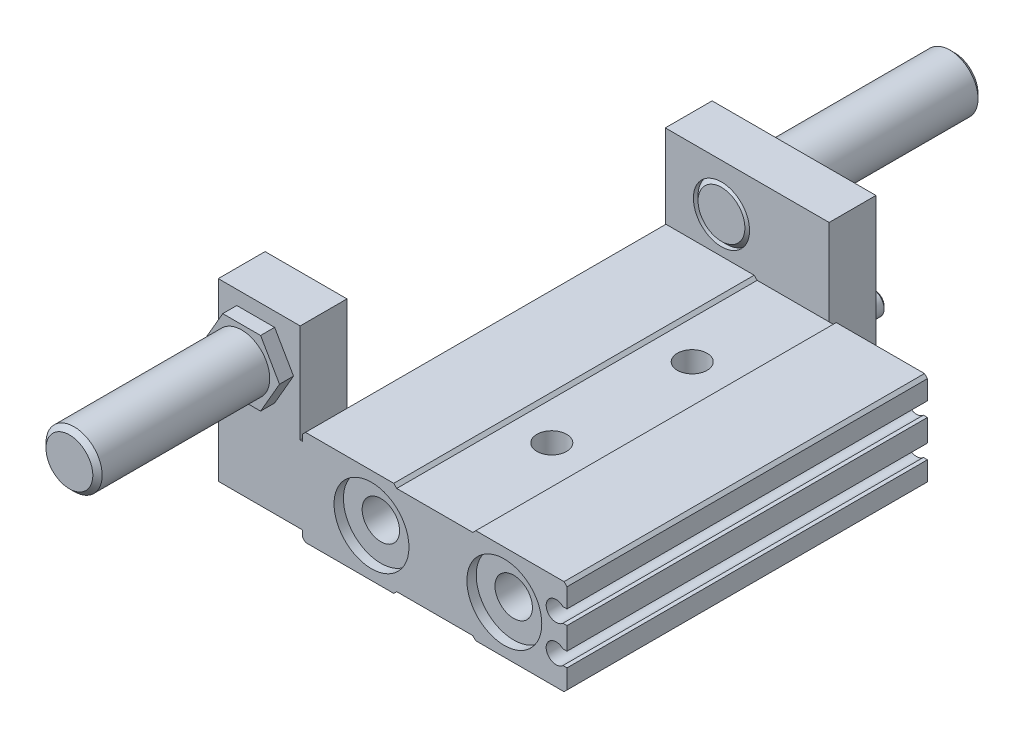
SolidWorks part; units mm, degrees
ref_plane "Front" through (0, 0, 0) normal (0, 0, 1) x (1, 0, 0)
ref_plane "Top" through (0, 0, 0) normal (0, 1, 0) x (1, 0, 0)
ref_plane "Right" through (0, 0, 0) normal (1, 0, 0) x (0, 0, -1)
ref_plane "Plane4" through (0, 0, 0) normal (0, 0, 1) x (-1, 0, 0)
sketch "Sketch1" plane through (0, 0, 51.15) normal (0, 0, 1) x (-1, 0, 0)
  line L0 (27.615, 10.1854) -> (28.25, 9.5504)
  line L1 (-8.128, 9.5504) -> (8.128, 9.5504)
  line L2 (27.615, 10.1854) -> (8.763, 10.1854)
  line L3 (-8.763, 10.1854) -> (-27.615, 10.1854)
  line L4 (8.128, 9.5504) -> (8.763, 10.1854)
  line L5 (-8.128, 9.5504) -> (-8.763, 10.1854)
  line L6 (-28.25, 9.5504) -> (-28.25, 5.4483)
  line L7 (-28.25, -9.5504) -> (-27.615, -10.1854)
  line L8 (-8.128, -9.5504) -> (-8.763, -10.1854)
  line L9 (-28.25, 2.3749) -> (-28.25, -2.3749)
  line L10 (-28.25, -5.4483) -> (-28.25, -9.5504)
  line L11 (-28.25, 9.5504) -> (-27.615, 10.1854)
  line L12 (28.25, 9.5504) -> (28.25, -9.5504)
  line L14 (-50, 0) -> (50, 0) construction
  line L15 (-8.763, -10.1854) -> (-27.615, -10.1854)
  line L16 (-27.3844, -5.4483) -> (-28.25, -5.4483)
  line L18 (-8.128, -9.5504) -> (8.128, -9.5504)
  line L19 (8.128, -9.5504) -> (8.763, -10.1854)
  line L20 (28.25, -9.5504) -> (27.615, -10.1854)
  line L22 (-28.25, 0) -> (28.25, 0) construction
  line L23 (0, 0) -> (0, 9.5504) construction
  line L26 (27.615, -10.1854) -> (8.763, -10.1854)
  line L27 (-27.3844, -2.3749) -> (-28.25, -2.3749)
  line L28 (-27.3844, 2.3749) -> (-28.25, 2.3749)
  line L29 (-27.3844, 5.4483) -> (-28.25, 5.4483)
  arc A0 (-27.3844, 2.3749) -> (-27.3844, 5.4483) centre (-25.9227, 3.9116) ccw
  arc A1 (-27.3844, -5.4483) -> (-27.3844, -2.3749) centre (-25.9227, -3.9116) ccw
  circle A2 centre (-14.859, 0) radius 11.7348 construction
  dimension "D5" = 4.2418
  dimension "D9" = 3.9116
  dimension "D4" = 11.7348
  dimension "D1" = 20.3708
  dimension "D2" = 45
  dimension "D3" = 0.635
  dimension "D6" = 17.526
  dimension "D7" = 14.859
  dimension "D8" = 3.0734
extrude "Base-Extrude" add sketch "Sketch1" along normal up to surface (77 mm away)
ref_plane "Plane8" through (0, 0, 49.15) normal (0, 0, 1) x (1, 0, 0)
sketch "Sketch2" plane through (0, 0, 51.15) normal (0, 0, -1) x (-1, 0, 0)
  line L0 (41.0206, 0) -> (-41.0206, 0) construction
  line L5 (0, 9.5504) -> (0, -9.5504) construction
  line L6 (8.128, 9.5504) -> (-8.128, 9.5504) construction
  line L7 (-8.128, -9.5504) -> (8.128, -9.5504) construction
  circle A0 centre (-14.859, 0) radius 8
  circle A1 centre (13.5128, 0) radius 8
  dimension "D1" = 16
  dimension "D3" = 14.859
  dimension "D2" = 28.3718
extrude "Cut-Extrude1" cut sketch "Sketch2" along normal up to surface (75.7 mm away)
sketch "Sketch4" plane through (0, 0, 49.15) normal (0, 0, 1) x (1, 0, 0)
  circle A2 centre (14.859, 0) radius 8 construction
  circle A3 centre (-13.5128, 0) radius 8 construction
  circle A4 centre (14.859, 0) radius 8
  circle A5 centre (-13.5128, 0) radius 8
extrude "Boss-Extrude1" add sketch "Sketch4" against normal blind 10
sketch "Sketch19" plane through (0, 0, 49.15) normal (0, 0, 1) x (1, 0, 0)
  circle A0 centre (14.859, 0) radius 4
  circle A1 centre (-13.5128, 0) radius 4
  circle A2 centre (-13.5128, 0) radius 8 construction
  circle A3 centre (14.859, 0) radius 8 construction
  dimension "D1" = 8
extrude "Cut-Extrude3" cut sketch "Sketch19" against normal up to next
hole_wizard "1/4-20 Tapped Hole1" positions "Sketch21" profile "Sketch20" tap size "1/4-20" standard "Ansi Inch"
sketch "Sketch21" plane through (0, -9.5504, 0) normal (0, -1, 0) x (1, 0, 0)
  point P0 (0, 26.15)
  point P1 (0, -3.85)
sketch "Sketch20" plane through (0, -9.5504, 26.15) normal (1, 0, 0) x (0, 0, -1)
  line L0 (0, 0) -> (0, 27.6958)
  line L1 (0, 27.6958) -> (2.5527, 26.162)
  line L2 (2.5527, 26.162) -> (2.5527, 19.812)
  line L3 (2.5527, 19.812) -> (3.175, 19.812)
  line L4 (3.175, 19.812) -> (3.175, 0)
  line L5 (3.175, 0) -> (0, 0)
  line L10 (0, 27.6958) -> (-2.5527, 26.162) construction
  line L11 (0, -6.35) -> (0, 107.95) construction
  dimension "Tap Drill Dia." = 5.1054
  dimension "Tap Drill Depth" = 26.162
  dimension "Thread Dia." = 6.35
  dimension "Thread Depth" = 19.812
  dimension "Drill Angle" = 118
hole_wizard "#8-32 Tapped Hole1" positions "Sketch23" profile "Sketch22" tap size "#8-32" standard "Ansi Inch"
sketch "Sketch23" plane through (0, 0, -25.85) normal (0, 0, -1) x (-1, 0, 0)
  line L0 (8.763, -10.1854) -> (27.615, -10.1854) construction
  point P0 (25, -5.6854)
  point P1 (25, 5.3146)
  point P2 (-4, -5.6854)
  point P3 (-4, 5.3146)
  dimension "D1" = 4.5
  dimension "D2" = 11
  dimension "D3" = 29
  dimension "D4" = 25
sketch "Sketch22" plane through (-25, -5.6854, -25.85) normal (1, 0, 0) x (0, 1, 0)
  line L0 (0, 0) -> (0, 11.8582)
  line L1 (0, 11.8582) -> (1.7272, 10.8204)
  line L2 (1.7272, 10.8204) -> (1.7272, 6.858)
  line L3 (1.7272, 6.858) -> (2.0828, 6.858)
  line L4 (2.0828, 6.858) -> (2.0828, 0)
  line L5 (2.0828, 0) -> (0, 0)
  line L10 (0, 11.8582) -> (-1.7272, 10.8204) construction
  line L11 (0, -6.35) -> (0, 107.95) construction
  dimension "Tap Drill Dia." = 3.4544
  dimension "Tap Drill Depth" = 10.8204
  dimension "Thread Dia." = 4.1656
  dimension "Thread Depth" = 6.858
  dimension "Drill Angle" = 118
hole_wizard "Hole1" positions "Sketch25" profile "Sketch24" legacy
sketch "Sketch25" plane through (0, -10.1854, 0) normal (0, -1, 0) x (1, 0, 0)
  point P0 (-24, 36.15)
sketch "Sketch24" plane through (-24, -10.1854, 36.15) normal (1, 0, 0) x (0, 0, -1)
  line L0 (0, 0) -> (0, 4)
  line L1 (0, 4) -> (2.5, 4)
  line L2 (2.5, 4) -> (2.5, 0)
  line L3 (2.5, 0) -> (0, 0)
  line L4 (0, 110) -> (0, -10) construction
  dimension "Diameter" = 5
  dimension "Depth" = 4
sketch "Sketch27" plane through (0, -10.1854, 0) normal (0, -1, 0) x (1, 0, 0)
  line L0 (-28.25, 1.15) -> (-24, 1.15) construction
  line L1 (-28.25, 51.15) -> (-28.25, -25.85) construction
  line L2 (-28.25, 4.15) -> (-24, 4.15) construction
  line L3 (-28.25, -1.85) -> (-24, -1.85) construction
  line L4 (-26.5, 1.65) -> (-26.5, 0.65)
  line L5 (-21.5, 1.65) -> (-21.5, 0.65)
  arc A0 (-26.5, 0.65) -> (-21.5, 0.65) centre (-24, 0.65) ccw
  arc A1 (-21.5, 1.65) -> (-26.5, 1.65) centre (-24, 1.65) ccw
  dimension "D1" = 5
  dimension "D2" = 6
extrude "Cut-Extrude4" cut sketch "Sketch27" against normal blind 4
hole_wizard "#10-32 Tapped Hole1" positions "Sketch29" profile "Sketch28" tap size "#10-32" standard "Ansi Inch"
sketch "Sketch29" plane through (-28.25, 0, 0) normal (-1, 0, 0) x (0, 0, 1)
  line L0 (51.15, 9.5504) -> (51.15, -9.5504) construction
  line L1 (-25.85, -9.5504) -> (-25.85, 9.5504) construction
  line L2 (-25.85, -10.1854) -> (51.15, -10.1854) construction
  point P0 (30.15, -0.1854)
  point P1 (-21.05, -0.1854)
  dimension "D1" = 21
  dimension "D2" = 4.8
  dimension "D3" = 10
sketch "Sketch28" plane through (-28.25, -0.1854, 30.15) normal (0, 1, 0) x (0, 0, 1)
  line L0 (0, 0) -> (0, 14.8277)
  line L1 (0, 14.8277) -> (2.0193, 13.6144)
  line L2 (2.0193, 13.6144) -> (2.0193, 9.652)
  line L3 (2.0193, 9.652) -> (2.413, 9.652)
  line L4 (2.413, 9.652) -> (2.413, 0)
  line L5 (2.413, 0) -> (0, 0)
  line L10 (0, 14.8277) -> (-2.0193, 13.6144) construction
  line L11 (0, -6.35) -> (0, 107.95) construction
  dimension "Tap Drill Dia." = 4.0386
  dimension "Tap Drill Depth" = 13.6144
  dimension "Thread Dia." = 4.826
  dimension "Thread Depth" = 9.652
  dimension "Drill Angle" = 118
sketch "Sketch30" plane through (0, 0, -25.85) normal (0, 0, -1) x (-1, 0, 0)
  line L0 (-8.128, -9.5504) -> (8.128, -9.5504) construction
  line L1 (-7.25, 27.9496) -> (27.75, 27.9496)
  line L2 (-7.25, 27.9496) -> (-7.25, -9.0504)
  line L3 (-7.25, -9.0504) -> (27.75, -9.0504)
  line L4 (27.75, 27.9496) -> (27.75, -9.0504)
  line L5 (28.25, -9.5504) -> (28.25, 9.5504) construction
  dimension "D1" = 0.5
  dimension "D2" = 0.5
  dimension "D3" = 37
  dimension "D4" = 35
extrude "Boss-Extrude2" add sketch "Sketch30" along normal blind 10
sketch "Sketch31" plane through (0, 0, -35.85) normal (0, 0, -1) x (-1, 0, 0)
  line L0 (23.8329, 17.9496) -> (19.7915, 24.9496)
  line L1 (19.7915, 24.9496) -> (11.7085, 24.9496)
  line L2 (11.7085, 24.9496) -> (7.6671, 17.9496)
  line L3 (7.6671, 17.9496) -> (11.7085, 10.9496)
  line L4 (11.7085, 10.9496) -> (19.7915, 10.9496)
  line L5 (19.7915, 10.9496) -> (23.8329, 17.9496)
  line L6 (27.75, 27.9496) -> (-7.25, 27.9496) construction
  line L7 (27.75, -9.0504) -> (27.75, 27.9496) construction
  circle A0 centre (15.75, 17.9496) radius 8.0829 construction
  dimension "D1" = 10
  dimension "D2" = 12
  dimension "D3" = 14
extrude "Boss-Extrude3" add sketch "Sketch31" along normal blind 3
sketch "Sketch35" plane through (0, 0, -35.85) normal (0, 0, -1) x (-1, 0, 0)
  circle A0 centre (25, 5.3146) radius 2.5
  circle A1 centre (-4, 5.3146) radius 2.5
  circle A2 centre (-4, -5.6854) radius 2.5
  circle A3 centre (25, -5.6854) radius 2.5
  circle A4 centre (25, -5.6854) radius 2.0828 construction
  circle A7 centre (-4, 5.3146) radius 2.0828 construction
  circle A8 centre (-4, -5.6854) radius 2.0828 construction
  circle A9 centre (25, 5.3146) radius 2.0828 construction
  dimension "D1" = 5
extrude "Boss-Extrude5" add sketch "Sketch35" along normal blind 3
chamfer "Chamfer2" distance 0.5 angle 45 4 edges at (-27.5, 5.3146, -38.85) (-27.5, -5.6854, -38.85) (1.5, -5.6854, -38.85) (1.5, 5.3146, -38.85)
ref_plane "Plane9" through (0, 0, 41.15) normal (0, 0, 1) x (1, 0, 0)
sketch "Sketch36" plane through (0, 0, 41.15) normal (0, 0, 1) x (1, 0, 0)
  line L0 (-28.75, 29.3146) -> (-28.75, 8.1854)
  line L1 (-46.25, 29.3146) -> (-28.75, 29.3146)
  line L2 (-46.25, 29.3146) -> (-46.25, -8.1854)
  line L3 (-46.25, -8.1854) -> (-28.25, -8.1854)
  line L4 (-28.25, 8.1854) -> (-28.25, -8.1854)
  line L5 (-28.75, 8.1854) -> (-28.25, 8.1854)
  line L7 (-28.25, 28.8146) -> (-28.25, -7.6854) construction
  line L8 (-27.615, -10.1854) -> (-8.763, -10.1854) construction
  line L11 (-27.1533, 10.1854) -> (-28.25, 10.1854) construction
  dimension "D1" = 18
  dimension "D2" = 0.5
  dimension "D3" = 37.5
  dimension "D4" = 2
  dimension "D5" = 2
extrude "Boss-Extrude6" add sketch "Sketch36" along normal blind 10
sketch "Sketch37" plane through (0, 0, 51.15) normal (0, 0, 1) x (1, 0, 0)
  line L0 (-46.25, 29.3146) -> (-46.25, -8.1854) construction
  line L1 (-34.2085, 26.3146) -> (-42.2915, 26.3146)
  line L2 (-42.2915, 26.3146) -> (-46.3329, 19.3146)
  line L3 (-46.3329, 19.3146) -> (-42.2915, 12.3146)
  line L4 (-42.2915, 12.3146) -> (-34.2085, 12.3146)
  line L5 (-34.2085, 12.3146) -> (-30.1671, 19.3146)
  line L8 (-30.1671, 19.3146) -> (-34.2085, 26.3146)
  line L9 (-28.75, 29.3146) -> (-46.25, 29.3146) construction
  circle A0 centre (-38.25, 19.3146) radius 7 construction
  dimension "D1" = 8
  dimension "D2" = 10
  dimension "D3" = 14
extrude "Boss-Extrude7" add sketch "Sketch37" along normal blind 3
sketch "Sketch38" plane through (0, 0, 54.15) normal (0, 0, 1) x (1, 0, 0)
  line L0 (-30.1671, 19.3146) -> (-34.2085, 26.3146) construction
  line L1 (-46.3329, 19.3146) -> (-42.2915, 12.3146) construction
  line L2 (-34.2085, 26.3146) -> (-42.2915, 26.3146) construction
  circle A0 centre (-38.25, 19.3146) radius 7 construction
  circle A1 centre (-38.25, 19.3146) radius 6
  dimension "D1" = 12
ref_plane "Plane11" through (0, 19.3146, 0) normal (0, 1, 0) x (-1, 0, 0)
extrude "Cut-Extrude7" cut sketch "Sketch38" against normal up to next
sketch "Sketch44" plane through (0, 19.3146, 0) normal (0, 1, 0) x (-1, 0, 0)
  line L0 (38.25, 54.15) -> (38.25, 41.15) construction
  line L1 (34.2085, 54.15) -> (42.2915, 54.15) construction
  line L2 (9.7125, 41.15) -> (-9.7125, 41.15) construction
  line L4 (38.25, 90.95) -> (44.25, 90.95)
  line L5 (38.25, 90.95) -> (38.25, 41.15)
  line L6 (38.25, 41.15) -> (43.25, 41.15)
  line L7 (44.25, 90.95) -> (44.25, 42.15)
  line L8 (44.25, 42.15) -> (43.25, 41.15)
  line L10 (44.25, 41.15) -> (44.25, 54.15) construction
  line L11 (28.75, 41.15) -> (46.25, 41.15) construction
  line L12 (28.75, 51.15) -> (46.25, 51.15) construction
  dimension "D1" = 39.8
  dimension "D2" = 45
  dimension "D3" = 1
revolve "Boss-Revolve1" add sketch "Sketch44" angle 360 about L0
sketch "Sketch46" plane through (0, 0, -38.85) normal (0, 0, -1) x (-1, 0, 0)
  line L0 (23.8329, 17.9496) -> (19.7915, 24.9496) construction
  line L1 (11.7085, 10.9496) -> (19.7915, 10.9496) construction
  line L2 (11.7085, 24.9496) -> (7.6671, 17.9496) construction
  circle A0 centre (15.75, 17.9496) radius 7 construction
  circle A1 centre (15.75, 17.9496) radius 6
  dimension "D1" = 12
extrude "Cut-Extrude8" cut sketch "Sketch46" against normal up to next
ref_plane "Plane12" through (0, 17.9496, 0) normal (0, 1, 0) x (-1, 0, 0)
sketch "Sketch47" plane through (0, 17.9496, 0) normal (0, 1, 0) x (-1, 0, 0)
  line L0 (27.75, -25.85) -> (-7.25, -25.85) construction
  line L2 (21.75, -38.85) -> (21.75, -25.85) construction
  line L3 (20.75, -25.85) -> (15.75, -25.85)
  line L4 (15.75, -25.85) -> (15.75, -75.65)
  line L5 (21.75, -75.65) -> (21.75, -26.85)
  line L6 (15.75, -25.85) -> (15.75, -75.65) construction
  line L7 (15.75, -75.65) -> (21.75, -75.65)
  line L8 (21.75, -26.85) -> (20.75, -25.85)
  line L9 (27.75, -35.85) -> (-7.25, -35.85) construction
  line L10 (15.75, -25.85) -> (15.75, -38.85) construction
  dimension "D1" = 45
  dimension "D2" = 1
  dimension "D3" = 39.8
revolve "Boss-Revolve2" add sketch "Sketch47" angle 360 about L6
chamfer "Chamfer3" distance 1 angle 45 2 edges at (-9.75, 17.9496, -75.65) (-32.25, 19.3146, 90.95)
